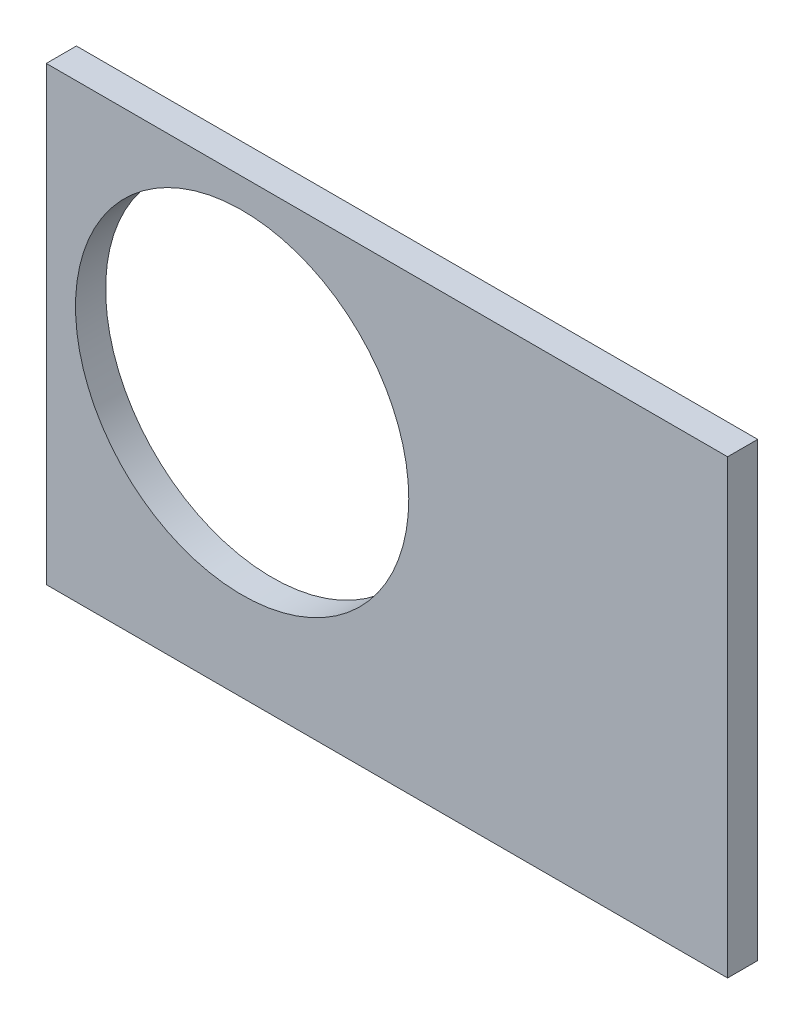
SolidWorks part; units mm, degrees
ref_plane "Front Plane" through (0, 0, 0) normal (0, 0, 1) x (1, 0, 0)
ref_plane "Top Plane" through (0, 0, 0) normal (0, 1, 0) x (1, 0, 0)
ref_plane "Right Plane" through (0, 0, 0) normal (1, 0, 0) x (0, 0, -1)
sketch "Sketch1" plane through (0, 0, 0) normal (0, 0, 1) x (1, 0, 0)
  line L0 (95.9485, -41.148) -> (95.9485, 111.379) construction
  line L1 (-41.275, 41.275) -> (102.2985, 41.275)
  line L2 (-41.275, 41.275) -> (-41.275, -53.848)
  line L3 (-41.275, -53.848) -> (102.2985, -53.848)
  line L4 (102.2985, 41.275) -> (102.2985, -53.848)
  circle A0 centre (0, 0) radius 35.1155 construction
  circle A1 centre (0, 0) radius 35.1155
  dimension "D3" = 41.275
  dimension "D1" = 41.275
  dimension "D2" = 12.7
  dimension "D4" = 6.35
extrude "Boss-Extrude1" add sketch "Sketch1" against normal blind 6.35
